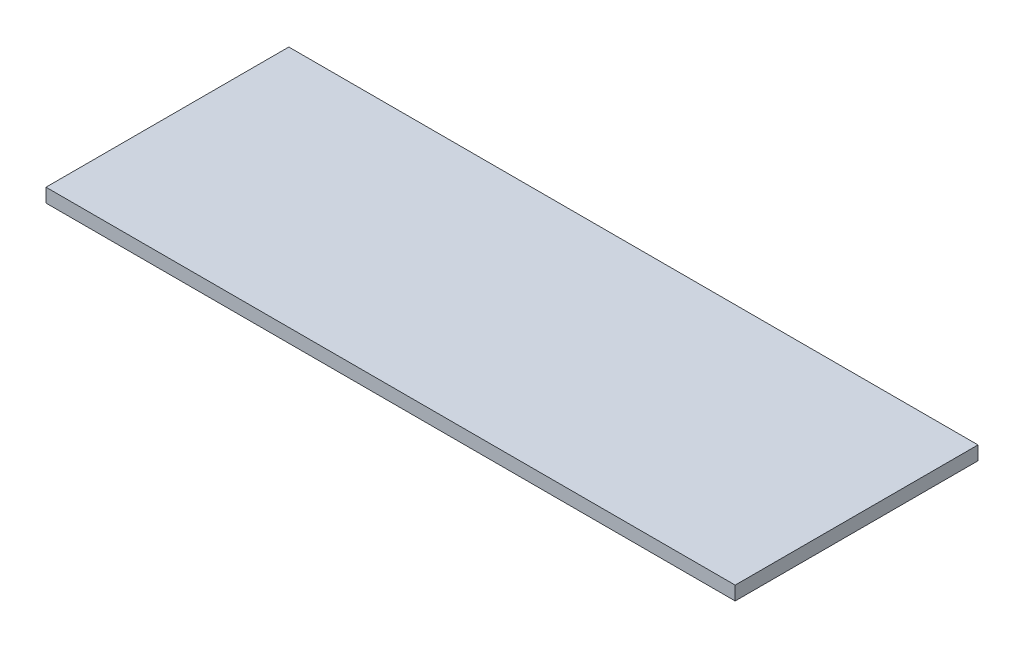
SolidWorks part; units mm, degrees
ref_plane "Front Plane" through (0, 0, 0) normal (0, 0, 1) x (1, 0, 0)
ref_plane "Top Plane" through (0, 0, 0) normal (0, 1, 0) x (1, 0, 0)
ref_plane "Right Plane" through (0, 0, 0) normal (1, 0, 0) x (0, 0, -1)
sketch "Sketch1" plane through (0, 0, 0) normal (0, 1, 0) x (1, 0, 0)
  line L1 (0, 0) -> (170, 0)
  line L2 (0, 0) -> (0, 140)
  line L3 (0, 140) -> (170, 140)
  line L4 (170, 0) -> (170, 140)
  dimension "D1" = 170
  dimension "D2" = 140
extrude "Boss-Extrude1" add sketch "Sketch1" along normal blind 4
sketch "Sketch2" plane through (0, 4, 0) normal (0, 1, 0) x (1, 0, 0)
  line L4 (112.9289, 112.9289) -> (127.0711, 127.0711)
  line L5 (134.1421, 130) -> (150, 130)
  line L6 (160, 120) -> (160, 20)
  line L12 (86.8495, 82.9289) -> (95.5064, 91.5858)
  line L13 (170, 0) -> (170, 140) construction
  line L14 (170, 140) -> (0, 140) construction
  line L15 (105.8579, 110) -> (0, 110)
  line L16 (0, 140) -> (0, 0) construction
  line L17 (94.0922, 95) -> (-94.0922, 95)
  line L18 (-80, 42.5) -> (80, 42.5) construction
  line L19 (0, 0) -> (170, 0) construction
  line L20 (150, 10) -> (114.1421, 10)
  line L21 (107.0711, 12.9289) -> (95.4289, 24.5711)
  line L22 (88.3579, 27.5) -> (0, 27.5)
  line L23 (-80, 44.5) -> (80, 44.5)
  line L26 (-80, 35) -> (80, 35) construction
  line L27 (-80, 37) -> (80, 37)
  line L28 (-80, 33) -> (80, 33)
  line L29 (-80, 40.5) -> (80, 40.5)
  line L32 (-80, 50) -> (80, 50) construction
  line L35 (-80, 52) -> (80, 52)
  line L38 (-80, 48) -> (80, 48)
  line L39 (-30.447, 80) -> (30.447, 80)
  line L40 (30.447, 80) -> (79.7785, 80)
  line L41 (-80, 57.5) -> (80, 57.5) construction
  line L42 (-80, 59.5) -> (80, 59.5)
  line L43 (-80, 55.5) -> (80, 55.5)
  line L44 (80, 65) -> (-80, 65) construction
  line L45 (80, 63) -> (-80, 63)
  line L46 (80, 67) -> (-80, 67)
  line L47 (-80, 72.5) -> (80, 72.5) construction
  line L48 (-80, 74.5) -> (80, 74.5)
  line L49 (-80, 70.5) -> (80, 70.5)
  line L50 (0, 170.2669) -> (0, -33.4511) construction
  line L51 (-86.8495, 82.9289) -> (-95.5064, 91.5858)
  line L52 (-30.447, 80) -> (-79.7785, 80)
  line L54 (100, 100.5425) -> (-100, 100.5425)
  line L55 (100, 100.5425) -> (100, 30.0785)
  line L56 (100, 30.0785) -> (-100, 30.0785)
  line L57 (-100, 100.5425) -> (-100, 30.0785)
  arc A2 (-80, 37) -> (-80, 33) centre (-80, 35) ccw
  arc A3 (80, 33) -> (80, 37) centre (80, 35) ccw
  arc A10 (150, 130) -> (160, 120) centre (150, 120) cw
  arc A11 (160, 20) -> (150, 10) centre (150, 20) cw
  arc A12 (-80, 44.5) -> (-80, 40.5) centre (-80, 42.5) ccw
  arc A13 (80, 40.5) -> (80, 44.5) centre (80, 42.5) ccw
  arc A14 (-80, 52) -> (-80, 48) centre (-80, 50) ccw
  arc A15 (80, 48) -> (80, 52) centre (80, 50) ccw
  arc A16 (-80, 59.5) -> (-80, 55.5) centre (-80, 57.5) ccw
  arc A17 (80, 55.5) -> (80, 59.5) centre (80, 57.5) ccw
  arc A18 (80, 63) -> (80, 67) centre (80, 65) ccw
  arc A19 (-80, 67) -> (-80, 63) centre (-80, 65) ccw
  arc A20 (-80, 74.5) -> (-80, 70.5) centre (-80, 72.5) ccw
  arc A21 (80, 70.5) -> (80, 74.5) centre (80, 72.5) ccw
  arc A22 (112.9289, 112.9289) -> (105.8579, 110) centre (105.8579, 120) cw
  arc A23 (127.0711, 127.0711) -> (134.1421, 130) centre (134.1421, 120) cw
  arc A24 (88.3579, 27.5) -> (95.4289, 24.5711) centre (88.3579, 17.5) cw
  arc A25 (107.0711, 12.9289) -> (114.1421, 10) centre (114.1421, 20) ccw
  arc A26 (95.5064, 91.5858) -> (94.0922, 95) centre (94.0922, 93) ccw
  arc A27 (86.8495, 82.9289) -> (79.7785, 80) centre (79.7785, 90) cw
  arc A28 (-95.5064, 91.5858) -> (-94.0922, 95) centre (-94.0922, 93) cw
  arc A29 (-86.8495, 82.9289) -> (-79.7785, 80) centre (-79.7785, 90) ccw
  point P20 (0, 42.5)
  point P27 (0, 35)
  point P34 (0, 50)
  point P41 (0, 57.5)
  point P46 (0, 65)
  point P55 (160, 130)
  point P63 (0, 72.5)
  point P70 (110, 110)
  point P73 (130, 130)
  point P76 (92.5, 27.5)
  point P79 (110, 10)
  point P82 (98.9206, 95)
  point P85 (83.9206, 80)
  point P92 (0, 95)
  point P96 (0, 80)
  line M35 (0, 140) -> (0, 0)
  dimension "D1" = 10
  dimension "D4" = 10
  dimension "D22" = 2
  dimension "D25" = 2
  dimension "D26" = 2
  dimension "D27" = 2
  dimension "D41" = 2
  dimension "D42" = 10
  dimension "D38" = 2
  dimension "D43" = 2
  dimension "D44" = 10
  dimension "D2" = 10
  dimension "D3" = 10
  dimension "D5" = 50
  dimension "D6" = 30
  dimension "D7" = 135
  dimension "D8" = 110
  dimension "D9" = 98.9206
  dimension "D10" = 21.2132
  dimension "D11" = 15
  dimension "D12" = 15
  dimension "D13" = 135
  dimension "D14" = 20
  dimension "D15" = 92.5
  dimension "D16" = 17.5
  dimension "D17" = 10
  dimension "D18" = 30
  dimension "D19" = 27.5
  dimension "D20" = 35
  dimension "D21" = 35
  dimension "D23" = 160
  dimension "D24" = 92.5
  dimension "D28" = 160
  dimension "D29" = 160
  dimension "D30" = 160
  dimension "D31" = 42.5
  dimension "D32" = 50
  dimension "D33" = 0
  dimension "D34" = 0
  dimension "D35" = 57.5
  dimension "D36" = 65
  dimension "D37" = 72.5
  dimension "D39" = 5.5
  dimension "D40" = 0
  dimension "D45" = 200
  dimension "D46" = 100
extrude "Boss-Extrude2" add sketch "Sketch2" along normal blind 4 contours L12 A27 L40 L39 L48 A21 L49 L46 A18 L45 L42 A17 L43 L35 A15 L38 L23 A13 L29 L27 A3 L28 L56 L55 L54 L17 A26 M35 | A29 L51 A28 L17 L54 L57 L56 L28 A2 L27 L29 A12 L23 L38 A14 L35 L43 A16 L42 L45 A19 L46 L49 A20 L48 L39 L52 M35 | A27 L12 A26 L17 L39 L40 M35 | L51 A29 L52 L39 L17 A28 M35
sketch "Sketch3" plane through (0, 4, 0) normal (0, 1, 0) x (1, 0, 0)
  line L1 (-9.0577, 1.0904) -> (170.9423, 1.0904)
  line L2 (-9.0577, 1.0904) -> (-9.0577, 171.0904)
  line L3 (-9.0577, 171.0904) -> (170.9423, 171.0904)
  line L4 (170.9423, 1.0904) -> (170.9423, 171.0904)
  dimension "D1" = 170
  dimension "D2" = 180
extrude "Cut-Extrude2" cut sketch "Sketch3" against normal blind 10
sketch "Sketch4" plane through (0, 4, 0) normal (0, 1, 0) x (1, 0, 0)
  line L1 (-13.5461, 11.9383) -> (194.7833, 11.9383)
  line L2 (-13.5461, 11.9383) -> (-13.5461, -13.8576)
  line L3 (-13.5461, -13.8576) -> (194.7833, -13.8576)
  line L4 (194.7833, 11.9383) -> (194.7833, -13.8576)
extrude "Cut-Extrude3" cut sketch "Sketch4" against normal blind 10
